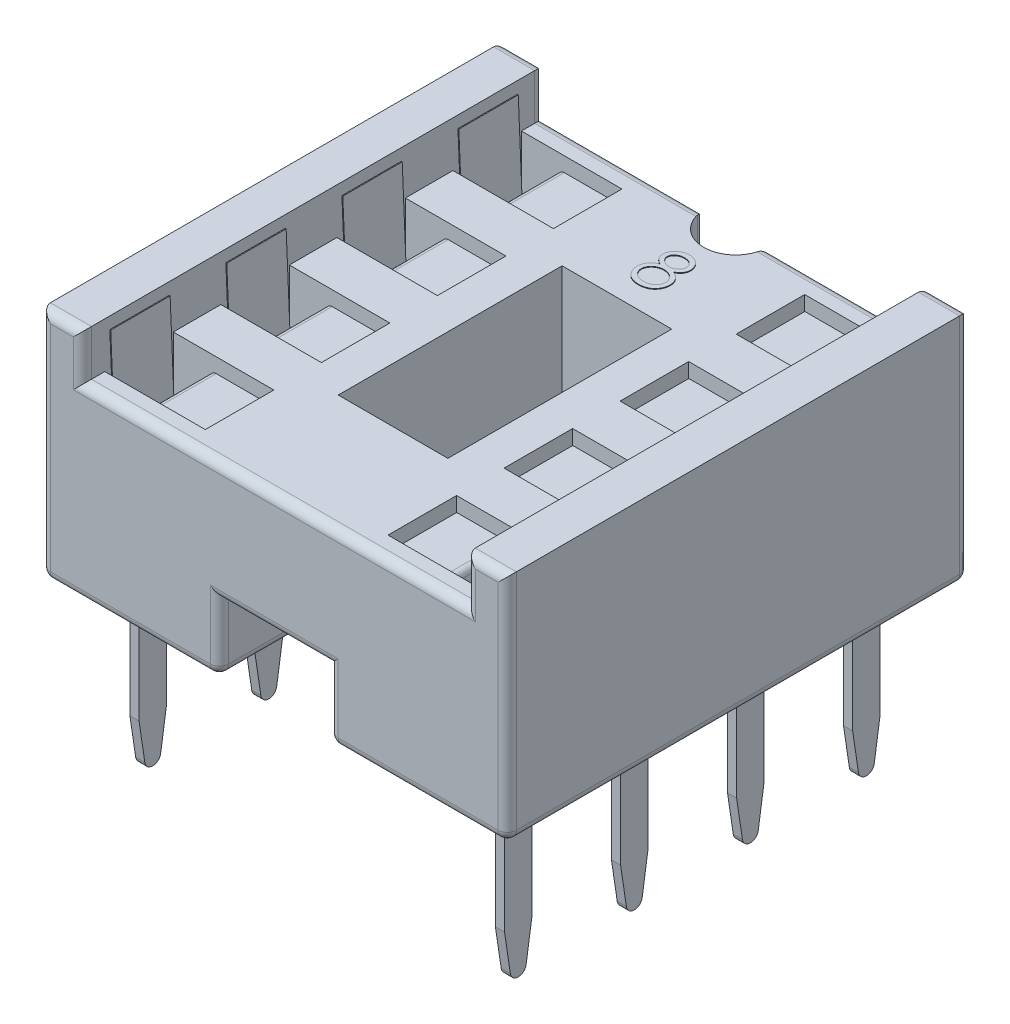
SolidWorks part; units mm, degrees
ref_plane "Front Plane" through (0, 0, 0) normal (0, 0, 1) x (1, 0, 0)
ref_plane "Top Plane" through (0, 0, 0) normal (0, 1, 0) x (1, 0, 0)
ref_plane "Right Plane" through (0, 0, 0) normal (1, 0, 0) x (0, 0, -1)
sketch "Sketch1" plane through (0, 0, 0) normal (0, 1, 0) x (1, 0, 0)
  line L1 (-5.1, -5.05) -> (5.1, -5.05)
  line L2 (-5.1, -5.05) -> (-5.1, 5.05)
  line L3 (-5.1, 5.05) -> (5.1, 5.05)
  line L4 (5.1, -5.05) -> (5.1, 5.05)
  line L5 (-5.1, -5.05) -> (5.1, 5.05) construction
  line L6 (-5.1, 5.05) -> (5.1, -5.05) construction
  line L7 (-1.2, -2.45) -> (1.2, -2.45)
  line L8 (-1.2, -2.45) -> (-1.2, 2.45)
  line L9 (-1.2, 2.45) -> (1.2, 2.45)
  line L10 (1.2, -2.45) -> (1.2, 2.45)
  line L11 (-1.2, -2.45) -> (1.2, 2.45) construction
  line L12 (-1.2, 2.45) -> (1.2, -2.45) construction
  point P0 (0, 0)
  point P5 (0, 0)
  dimension "D1" = 10.2
  dimension "D2" = 10.1
  dimension "D3" = 2.6
  dimension "D4" = 3.9
extrude "Boss-Extrude1" add sketch "Sketch1" along normal blind 5.1
sketch "Sketch2" plane through (0, 5.1, 0) normal (0, 1, 0) x (1, 0, 0)
  line L0 (5.1, 5.05) -> (-5.1, 5.05) construction
  line L1 (-4.2, -5.05) -> (4.2, -5.05)
  line L2 (-4.2, -5.05) -> (-4.2, 5.05)
  line L3 (-4.2, 5.05) -> (4.2, 5.05)
  line L4 (4.2, -5.05) -> (4.2, 5.05)
  line L5 (-4.2, -5.05) -> (4.2, 5.05) construction
  line L6 (-4.2, 5.05) -> (4.2, -5.05) construction
  line L7 (5.1, -5.05) -> (5.1, 5.05) construction
  point P0 (0, 0)
  dimension "D1" = 0.9
extrude "Cut-Extrude1" cut sketch "Sketch2" against normal blind 1
sketch "Sketch3" plane through (0, 4.1, 0) normal (0, 1, 0) x (1, 0, 0)
  line L0 (4.2, 5.05) -> (-4.2, 5.05) construction
  line L1 (-0.7, 5.05) -> (0.7, 5.05)
  arc A0 (0.7, 5.05) -> (-0.7, 5.05) centre (0, 5.05) cw
  dimension "D1" = 0.7
extrude "Cut-Extrude2" cut sketch "Sketch3" against normal up to surface (4.1 mm away) up to face at (0, 0, 0)
sketch "Sketch4" plane through (0, 0, -5.05) normal (0, 0, -1) x (-1, 0, 0)
  line L0 (-5.1, 0) -> (-0.7, 0) construction
  line L1 (-1.2, 0) -> (1.2, 0)
  line L2 (-1.2, 0) -> (-1.2, 1.5)
  line L3 (-1.2, 1.5) -> (1.2, 1.5)
  line L4 (1.2, 0) -> (1.2, 1.5)
  line L5 (1.2, 4.1) -> (1.2, 0) construction
  point P6 (0, 0)
  dimension "D2" = 1.5
extrude "Cut-Extrude3" cut sketch "Sketch4" against normal up to surface (10.1 mm away) up to face at (0, 3.575, 5.05)
sketch "Sketch5" plane through (0, 4.1, 0) normal (0, 1, 0) x (1, 0, 0)
  line L0 (-4.2, 5.05) -> (-4.2, -5.05) construction
  line L1 (-4.2, 4.56) -> (-2, 4.56)
  line L2 (-4.2, 4.56) -> (-4.2, 3.06)
  line L3 (-4.2, 3.06) -> (-2, 3.06)
  line L4 (-2, 4.56) -> (-2, 3.06)
  line L5 (0, 4.35) -> (0, -5.05) construction
  line L6 (-4.2, -5.05) -> (4.2, -5.05) construction
  line L7 (4.2, 4.56) -> (2, 4.56)
  line L8 (4.2, 4.56) -> (4.2, 3.06)
  line L9 (4.2, 3.06) -> (2, 3.06)
  line L10 (2, 4.56) -> (2, 3.06)
  line L11 (2, 2.02) -> (2, 0.52)
  line L12 (4.2, 0.52) -> (2, 0.52)
  line L13 (4.2, 2.02) -> (4.2, 0.52)
  line L14 (4.2, 2.02) -> (2, 2.02)
  line L15 (-2, 2.02) -> (-2, 0.52)
  line L16 (-4.2, 0.52) -> (-2, 0.52)
  line L17 (-4.2, 2.02) -> (-4.2, 0.52)
  line L18 (-4.2, 2.02) -> (-2, 2.02)
  line L19 (2, -0.52) -> (2, -2.02)
  line L20 (4.2, -2.02) -> (2, -2.02)
  line L21 (4.2, -0.52) -> (4.2, -2.02)
  line L22 (4.2, -0.52) -> (2, -0.52)
  line L23 (-2, -0.52) -> (-2, -2.02)
  line L24 (-4.2, -2.02) -> (-2, -2.02)
  line L25 (-4.2, -0.52) -> (-4.2, -2.02)
  line L26 (-4.2, -0.52) -> (-2, -0.52)
  line L27 (2, -3.06) -> (2, -4.56)
  line L28 (4.2, -4.56) -> (2, -4.56)
  line L29 (4.2, -3.06) -> (4.2, -4.56)
  line L30 (4.2, -3.06) -> (2, -3.06)
  line L31 (-2, -3.06) -> (-2, -4.56)
  line L32 (-4.2, -4.56) -> (-2, -4.56)
  line L33 (-4.2, -3.06) -> (-4.2, -4.56)
  line L34 (-4.2, -3.06) -> (-2, -3.06)
  line L35 (-2, 4.56) -> (-2, 5.05) construction
  line L36 (-0.7, 5.05) -> (-4.2, 5.05) construction
  line L37 (-2, -4.56) -> (-2, -5.05) construction
  arc A0 (-0.7, 5.05) -> (0.7, 5.05) centre (0, 5.05) ccw construction
  line M27 (-4.2, 5.05) -> (-4.2, -5.05)
  line M29 (4.2, -5.05) -> (4.2, 5.05)
  dimension "D1" = 1.5
  dimension "D2" = 2.2
  dimension "D3" = 4
extrude "Cut-Extrude4" cut sketch "Sketch5" against normal offset from surface (3.1 mm away) 1 contours L4 L1 L3 M27 | L18 L16 L15 M27 | L26 L24 L23 M27 | L34 L32 L31 M27 | L30 L27 L28 M29 | L22 L19 L20 M29 | L14 L11 L12 M29 | L7 L10 L9 M29 up to face at (-3.15, 0, 0)
sketch "Sketch6" plane through (0, 4.1, 0) normal (0, 1, 0) x (1, 0, 0)
  line L0 (-0.4, 2.95) -> (0.4, 2.95) construction
  line L1 (-0.4, 2.95) -> (-0.4, 4.05) construction
  line L2 (-0.4, 4.05) -> (0.4, 4.05) construction
  line L3 (0.4, 4.05) -> (0.4, 2.95) construction
  line L4 (0, 2.95) -> (0, 4.35) construction
  arc A0 (-0.7, 5.05) -> (0.7, 5.05) centre (0, 5.05) ccw construction
  arc A1 (-0.7, 5.05) -> (0.7, 5.05) centre (0, 5.05) ccw construction
  text T0 "8" font "Century Gothic" height in points 4
  point P10 (0, 4.35)
  dimension "D1" = 0.8
  dimension "D2" = 1.1
  dimension "D3" = 1.4
extrude "Boss-Extrude2" add sketch "Sketch6" along normal blind 0.015
sketch "Sketch7" plane through (0, 0, 0) normal (0, -1, 0) x (1, 0, 0)
  line L0 (0, 5.05) -> (0, -4.35) construction
  line L1 (1.2, 5.05) -> (-1.2, 5.05) construction
  line L3 (-4.1, 4.11) -> (-3.9, 4.11)
  line L4 (-4.1, 4.11) -> (-4.1, 3.51)
  line L5 (-4.1, 3.51) -> (-3.9, 3.51)
  line L6 (-3.9, 4.11) -> (-3.9, 3.51)
  line L7 (-4.1, 4.11) -> (-3.9, 3.51) construction
  line L8 (-4.1, 3.51) -> (-3.9, 4.11) construction
  line L9 (-5.1, -5.05) -> (-5.1, 5.05) construction
  line L10 (-4.1, 4.11) -> (-4.1, 5.05) construction
  line L11 (-5.1, 5.05) -> (-1.2, 5.05) construction
  line L12 (4.1, 4.11) -> (3.9, 4.11)
  line L13 (4.1, 4.11) -> (4.1, 3.51)
  line L14 (4.1, 3.51) -> (3.9, 3.51)
  line L15 (3.9, 4.11) -> (3.9, 3.51)
  line L16 (4.1, 1.57) -> (3.9, 1.57)
  line L17 (3.9, 1.57) -> (3.9, 0.97)
  line L18 (4.1, 0.97) -> (3.9, 0.97)
  line L19 (4.1, 1.57) -> (4.1, 0.97)
  line L20 (-3.9, 1.57) -> (-3.9, 0.97)
  line L21 (-4.1, 0.97) -> (-3.9, 0.97)
  line L22 (-4.1, 1.57) -> (-4.1, 0.97)
  line L23 (-4.1, 1.57) -> (-3.9, 1.57)
  line L24 (4.1, -0.97) -> (3.9, -0.97)
  line L25 (3.9, -0.97) -> (3.9, -1.57)
  line L26 (4.1, -1.57) -> (3.9, -1.57)
  line L27 (4.1, -0.97) -> (4.1, -1.57)
  line L28 (-3.9, -0.97) -> (-3.9, -1.57)
  line L29 (-4.1, -1.57) -> (-3.9, -1.57)
  line L30 (-4.1, -0.97) -> (-4.1, -1.57)
  line L31 (-4.1, -0.97) -> (-3.9, -0.97)
  line L32 (4.1, -3.51) -> (3.9, -3.51)
  line L33 (3.9, -3.51) -> (3.9, -4.11)
  line L34 (4.1, -4.11) -> (3.9, -4.11)
  line L35 (4.1, -3.51) -> (4.1, -4.11)
  line L36 (-3.9, -3.51) -> (-3.9, -4.11)
  line L37 (-4.1, -4.11) -> (-3.9, -4.11)
  line L38 (-4.1, -3.51) -> (-4.1, -4.11)
  line L39 (-4.1, -3.51) -> (-3.9, -3.51)
  line L40 (4.1, 4.11) -> (4.1, 1.57) construction
  line L41 (-4.1, -4.11) -> (-4.1, -5.05) construction
  line L42 (-1.2, -5.05) -> (-5.1, -5.05) construction
  arc A0 (0.7, -5.05) -> (-0.7, -5.05) centre (0, -5.05) ccw construction
  point P7 (-4, 3.81)
  dimension "D1" = 1
  dimension "D2" = 0.6
  dimension "D3" = 0.2
  dimension "D4" = 4
  dimension "D5" = 2.54
extrude "Boss-Extrude3" add sketch "Sketch7" along normal blind 3.6
sketch "Sketch8" plane through (-4.1, 0, 0) normal (-1, 0, 0) x (0, 0, 1)
  line L0 (-3.51, -3.6) -> (-4.11, -3.6) construction
  line L1 (-3.81, -3.425) -> (-3.81, -2.6) construction
  line L2 (-4.11, -2.6) -> (-3.9831, -3.4508)
  line L3 (-4.11, -3.6) -> (-4.11, 0) construction
  line L4 (-3.6369, -3.4508) -> (-3.51, -2.6)
  line L5 (-3.51, -3.6) -> (-3.51, 0) construction
  line L6 (-3.51, -2.6) -> (-4.11, -2.6) construction
  line L7 (-4.11, -2.6) -> (-4.11, -3.6)
  line L8 (-4.11, -3.6) -> (-3.51, -3.6)
  line L9 (-3.51, -3.6) -> (-3.51, -2.6)
  arc A0 (-3.9831, -3.4508) -> (-3.6369, -3.4508) centre (-3.81, -3.425) ccw
  line M11 (-4.11, 0) -> (-4.11, -3.6)
  line M12 (-4.11, -3.6) -> (-3.51, -3.6)
  line M13 (-3.51, -3.6) -> (-3.51, 0)
  dimension "D1" = 0.35
  dimension "D2" = 1
extrude "Cut-Extrude5" cut sketch "Sketch8" against normal up to surface (8.2 mm away) contours A0 L2 M11 M12 | A0 L8 L4 M13 up to face at (4.1, -1.8, -3.81)
pattern_linear "LPattern1" count 4 spacing 2.54 along (0, 0, 1) of "Cut-Extrude5"
fillet "Fillet1" radius 0.2 32 edges at (5.1, 2.55, -5.05) (4.65, 5.1, -5.05) (4.2, 4.6, -5.05) (2.45, 4.1, -5.05) (0.7, 2.8, -5.05) (-0.7, 2.8, -5.05) (0.95, 1.5, -5.05) (1.2, 0.75, -5.05) (3.15, 0, -5.05) (-1.2, 0.75, 5.05) (-3.15, 0, 5.05) (-5.1, 2.55, 5.05) (-4.65, 5.1, 5.05) (-4.2, 4.6, 5.05) (0, 4.1, 5.05) (4.2, 4.6, 5.05) (4.65, 5.1, 5.05) (5.1, 2.55, 5.05) (3.15, 0, 5.05) (1.2, 0.75, 5.05) (0, 1.5, 5.05) (-2.45, 4.1, -5.05) (-4.2, 4.6, -5.05) (-4.65, 5.1, -5.05) (-5.1, 2.55, -5.05) (-3.15, 0, -5.05) (-1.2, 0.75, -5.05) (-0.95, 1.5, -5.05) (-1.2, 0, 0) (-5.1, 0, 0) (1.2, 0, 0) (5.1, 0, 0)
ref_plane "Plane3" through (0, 0, -3.81) normal (0, 0, 1) x (1, 0, 0)
sketch "Sketch11" plane through (0, 0, -3.81) normal (0, 0, 1) x (1, 0, 0)
  line L0 (-4.1, 4.85) -> (-3.9554, 1.5391)
  line L2 (-4.2, 1) -> (-4.2, 4.1) construction
  line L3 (-4.2, 5.1) -> (-5.1, 5.1) construction
  line L4 (-2.1, 3.95) -> (-3.1592, 3.95)
  line L6 (-3.359, 3.7587) -> (-3.4559, 1.5391)
  line L7 (-0.6708, 4.1) -> (-4.2, 4.1) construction
  line L8 (-4.2, 4.1) -> (-4.2, 5.1) construction
  line L9 (-3.7057, 1.3) -> (-3.0333, 1.3) construction
  line L10 (-4.2, 1) -> (-2, 1) construction
  line L11 (-2, 1) -> (-2, 4.1) construction
  arc A0 (-3.9554, 1.5391) -> (-3.4559, 1.5391) centre (-3.7057, 1.55) ccw
  arc A1 (-3.1592, 3.95) -> (-3.359, 3.7587) centre (-3.1592, 3.75) ccw
  dimension "D3" = 0.5
  dimension "D6" = 0.2
  dimension "D1" = 2.5
  dimension "D2" = 0.25
  dimension "D4" = 92.5
  dimension "D5" = 0.15
  dimension "D7" = 0.3
  dimension "D8" = 0.1
  dimension "D9" = 0.1
ref_plane "Plane5" through (0, 4.85, 0) normal (0, 1, 0) x (1, 0, 0)
sketch "Sketch13" plane through (0, 4.85, 0) normal (0, 1, 0) x (1, 0, 0)
  line L0 (-4.2, 4.56) -> (-2, 4.56) construction
  line L1 (-4.17, 4.46) -> (-4.19, 4.46)
  line L2 (-4.17, 4.46) -> (-4.17, 3.16)
  line L3 (-4.17, 3.16) -> (-4.19, 3.16)
  line L4 (-4.19, 4.46) -> (-4.19, 3.16)
  line L5 (-4.18, 4.46) -> (-4.18, 4.56) construction
  line L6 (-4.18, 3.16) -> (-4.18, 3.06) construction
  line L7 (-4.2, 3.06) -> (-2, 3.06) construction
  line L8 (-4.2, 4.85) -> (-4.2, -4.85) construction
  point P15 (-4.18, 4.46)
  dimension "D1" = 0.01
  dimension "D2" = 0.02
  dimension "D3" = 0.1
sweep "Sweep7" add profiles "Sketch13" path "Sketch11"
pattern_linear "LPattern2" count 4 spacing 2.54 along (0, 0, 1) of bodies 110
mirror "Mirror4" about plane through (0, 0, 0) normal (1, 0, 0) of bodies 110 113 114 115 116
